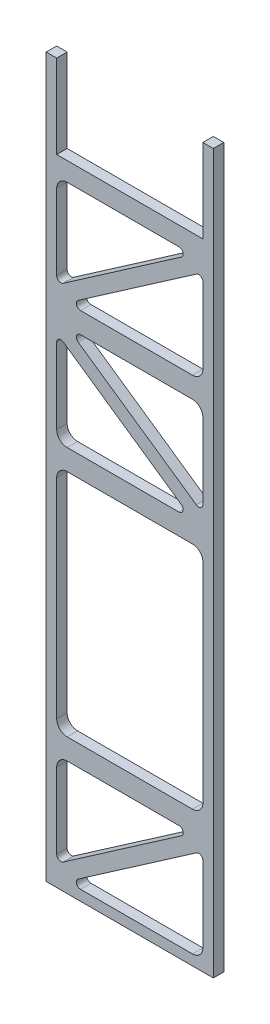
SolidWorks part; units mm, degrees
material "Balsa"
ref_plane "Front Plane" through (0, 0, 0) normal (0, 0, 1) x (1, 0, 0)
ref_plane "Top Plane" through (0, 0, 0) normal (0, 1, 0) x (1, 0, 0)
ref_plane "Right Plane" through (0, 0, 0) normal (1, 0, 0) x (0, 0, -1)
sketch "Model" plane through (0, 0, 0) normal (0, 0, 1) x (1, 0, 0)
  line L0 (-80.7688, 311.15) -> (-12.7, 311.15)
  line L1 (-10.3358, 365.5406) -> (-82.2146, 315.7784)
  line L2 (-6.35, 317.5) -> (-6.35, 363.4522)
  line L3 (-95.25, 287.2522) -> (-95.25, 241.3)
  line L4 (-19.3854, 239.5784) -> (-91.2642, 289.3406)
  line L5 (-88.9, 234.95) -> (-20.8312, 234.95)
  line L6 (-80.7688, 158.75) -> (-12.7, 158.75)
  line L7 (-10.3358, 213.1406) -> (-82.2146, 163.3784)
  line L8 (-6.35, 165.1) -> (-6.35, 211.0522)
  line L9 (-20.8312, 222.25) -> (-88.9, 222.25)
  line L10 (-91.2642, 167.8594) -> (-19.3854, 217.6216)
  line L11 (-95.25, 215.9) -> (-95.25, 169.9478)
  line L12 (-82.2146, 293.8216) -> (-10.3358, 244.0594)
  line L13 (-12.7, 298.45) -> (-80.7688, 298.45)
  line L14 (-6.35, 246.1478) -> (-6.35, 292.1)
  line L15 (-95.25, 134.8522) -> (-95.25, 88.9)
  line L16 (-19.3854, 87.1784) -> (-91.2642, 136.9406)
  line L17 (-88.9, 82.55) -> (-20.8312, 82.55)
  line L18 (-80.7688, 6.35) -> (-12.7, 6.35)
  line L19 (-10.3358, 60.7406) -> (-82.2146, 10.9784)
  line L20 (-6.35, 12.7) -> (-6.35, 58.6522)
  line L21 (-20.8312, 69.85) -> (-88.9, 69.85)
  line L22 (-91.2642, 15.4594) -> (-19.3854, 65.2216)
  line L23 (-95.25, 63.5) -> (-95.25, 17.5478)
  line L24 (-20.8312, 374.65) -> (-88.9, 374.65)
  line L25 (-91.2642, 320.2594) -> (-19.3854, 370.0216)
  line L26 (-95.25, 368.3) -> (-95.25, 322.3478)
  line L27 (-82.2146, 141.4216) -> (-10.3358, 91.6594)
  line L28 (-12.7, 146.05) -> (-80.7688, 146.05)
  line L29 (-6.35, 93.7478) -> (-6.35, 139.7)
  line L30 (-95.25, 386.08) -> (-6.35, 386.08)
  line L31 (-95.25, 386.08) -> (-95.25, 436.88)
  line L32 (-101.6, 436.88) -> (-95.25, 436.88)
  line L33 (-101.6, 0) -> (-101.6, 436.88)
  line L34 (-101.6, 0) -> (0, 0)
  line L35 (0, 0) -> (0, 436.88)
  line L36 (-6.35, 436.88) -> (0, 436.88)
  line L37 (-6.35, 386.08) -> (-6.35, 436.88)
  arc A0 (-12.7, 311.15) -> (-6.35, 317.5) centre (-12.7, 317.5) ccw
  arc A1 (-82.2146, 315.7784) -> (-80.7688, 311.15) centre (-80.7688, 313.69) ccw
  arc A2 (-6.35, 363.4522) -> (-10.3358, 365.5406) centre (-8.89, 363.4522) ccw
  arc A3 (-95.25, 241.3) -> (-88.9, 234.95) centre (-88.9, 241.3) ccw
  arc A4 (-91.2642, 289.3406) -> (-95.25, 287.2522) centre (-92.71, 287.2522) ccw
  arc A5 (-20.8312, 234.95) -> (-19.3854, 239.5784) centre (-20.8312, 237.49) ccw
  arc A6 (-12.7, 158.75) -> (-6.35, 165.1) centre (-12.7, 165.1) ccw
  arc A7 (-82.2146, 163.3784) -> (-80.7688, 158.75) centre (-80.7688, 161.29) ccw
  arc A8 (-6.35, 211.0522) -> (-10.3358, 213.1406) centre (-8.89, 211.0522) ccw
  arc A9 (-88.9, 222.25) -> (-95.25, 215.9) centre (-88.9, 215.9) ccw
  arc A10 (-19.3854, 217.6216) -> (-20.8312, 222.25) centre (-20.8312, 219.71) ccw
  arc A11 (-95.25, 169.9478) -> (-91.2642, 167.8594) centre (-92.71, 169.9478) ccw
  arc A12 (-10.3358, 244.0594) -> (-6.35, 246.1478) centre (-8.89, 246.1478) ccw
  arc A13 (-80.7688, 298.45) -> (-82.2146, 293.8216) centre (-80.7688, 295.91) ccw
  arc A14 (-6.35, 292.1) -> (-12.7, 298.45) centre (-12.7, 292.1) ccw
  arc A15 (-95.25, 88.9) -> (-88.9, 82.55) centre (-88.9, 88.9) ccw
  arc A16 (-91.2642, 136.9406) -> (-95.25, 134.8522) centre (-92.71, 134.8522) ccw
  arc A17 (-20.8312, 82.55) -> (-19.3854, 87.1784) centre (-20.8312, 85.09) ccw
  arc A18 (-12.7, 6.35) -> (-6.35, 12.7) centre (-12.7, 12.7) ccw
  arc A19 (-82.2146, 10.9784) -> (-80.7688, 6.35) centre (-80.7688, 8.89) ccw
  arc A20 (-6.35, 58.6522) -> (-10.3358, 60.7406) centre (-8.89, 58.6522) ccw
  arc A21 (-88.9, 69.85) -> (-95.25, 63.5) centre (-88.9, 63.5) ccw
  arc A22 (-19.3854, 65.2216) -> (-20.8312, 69.85) centre (-20.8312, 67.31) ccw
  arc A23 (-95.25, 17.5478) -> (-91.2642, 15.4594) centre (-92.71, 17.5478) ccw
  arc A24 (-88.9, 374.65) -> (-95.25, 368.3) centre (-88.9, 368.3) ccw
  arc A25 (-19.3854, 370.0216) -> (-20.8312, 374.65) centre (-20.8312, 372.11) ccw
  arc A26 (-95.25, 322.3478) -> (-91.2642, 320.2594) centre (-92.71, 322.3478) ccw
  arc A27 (-10.3358, 91.6594) -> (-6.35, 93.7478) centre (-8.89, 93.7478) ccw
  arc A28 (-80.7688, 146.05) -> (-82.2146, 141.4216) centre (-80.7688, 143.51) ccw
  arc A29 (-6.35, 139.7) -> (-12.7, 146.05) centre (-12.7, 139.7) ccw
extrude "Boss-Extrude1" add sketch "Model" along normal blind 6.35
sketch "Sketch1" plane through (0, 0, 6.35) normal (0, 0, 1) x (1, 0, 0)
  line L0 (-95.25, 215.9) -> (-95.25, 169.9478) construction
  line L1 (-12.7, 82.55) -> (-88.9, 82.55)
  line L2 (-6.35, 88.9) -> (-6.35, 215.9)
  line L3 (-12.7, 222.25) -> (-88.9, 222.25)
  line L4 (-95.25, 88.9) -> (-95.25, 215.9)
  line L5 (-20.8312, 222.25) -> (-88.9, 222.25) construction
  line L6 (-88.9, 82.55) -> (-20.8312, 82.55) construction
  arc A0 (-88.9, 82.55) -> (-95.25, 88.9) centre (-88.9, 88.9) cw
  arc A1 (-88.9, 222.25) -> (-95.25, 215.9) centre (-88.9, 215.9) ccw
  arc A2 (-6.35, 215.9) -> (-12.7, 222.25) centre (-12.7, 215.9) ccw
  arc A3 (-12.7, 82.55) -> (-6.35, 88.9) centre (-12.7, 88.9) ccw
  point P14 (-95.25, 222.25)
  point P17 (-6.35, 222.25)
  dimension "D2" = 6.35
  dimension "D1" = 88.9
extrude "Cut-Extrude1" cut sketch "Sketch1" against normal up to surface (6.35 mm away) up to face at (-50.8, 314.96, 0)
equation "\"thick\"=0.25"
equation "\"D1@Boss-Extrude1\"=\"thick\""
